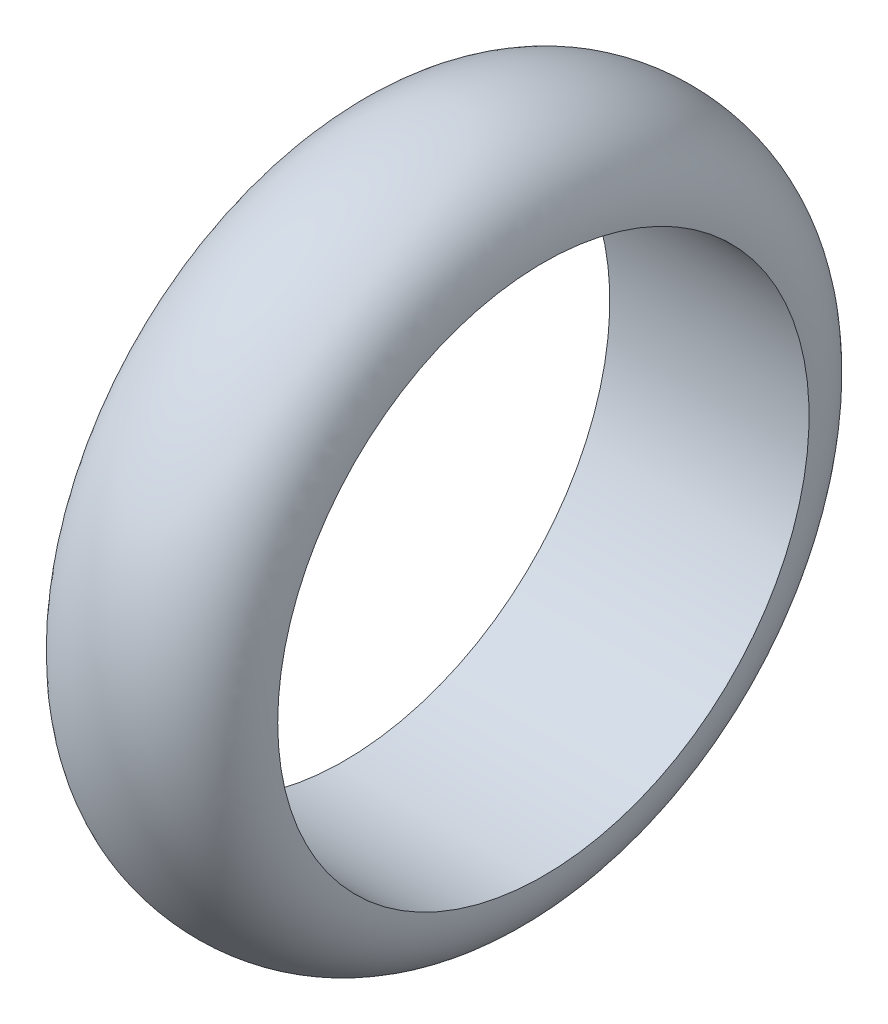
SolidWorks part; units mm, degrees
ref_plane "Front Plane" through (0, 0, 0) normal (0, 0, 1) x (1, 0, 0)
ref_plane "Top Plane" through (0, 0, 0) normal (0, 1, 0) x (1, 0, 0)
ref_plane "Right Plane" through (0, 0, 0) normal (1, 0, 0) x (0, 0, -1)
sketch "Sketch1" plane through (0, 0, 0) normal (0, 1, 0) x (1, 0, 0)
  line L0 (0, 0) -> (58.2083, 0) construction
  line L1 (0, 101.6) -> (76.2, 101.6)
  spline S0 degree 1 poles (0, 101.6) (76.2, 101.6) knots 0 0 1 1
  spline S1 degree 3 poles (0, 101.6) (0, 143.6532) (76.2, 144.2785) (76.2, 101.6) knots 0 0 0 0 1 1 1 1
  dimension "D1" = 76.2
  dimension "D2" = 101.6
revolve "Revolve1" add sketch "Sketch1" angle 360 about L0
